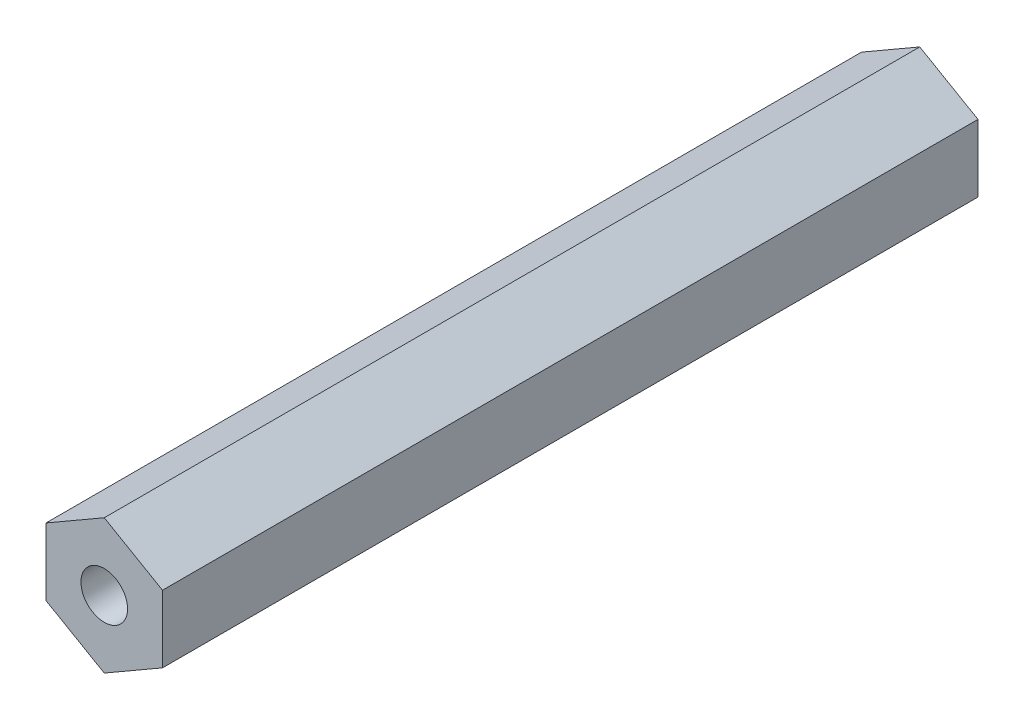
SolidWorks part; units mm, degrees
ref_plane "Front Plane" through (0, 0, 0) normal (0, 0, 1) x (1, 0, 0)
ref_plane "Top Plane" through (0, 0, 0) normal (0, 1, 0) x (1, 0, 0)
ref_plane "Right Plane" through (0, 0, 0) normal (1, 0, 0) x (0, 0, -1)
sketch "Sketch1" plane through (0, 0, 0) normal (0, 0, 1) x (1, 0, 0)
  line L1 (0, 2.8868) -> (-2.5, 1.4434)
  line L2 (-2.5, 1.4434) -> (-2.5, -1.4434)
  line L3 (-2.5, -1.4434) -> (0, -2.8868)
  line L4 (0, -2.8868) -> (2.5, -1.4434)
  line L5 (2.5, -1.4434) -> (2.5, 1.4434)
  line L6 (2.5, 1.4434) -> (0, 2.8868)
  circle A0 centre (0, 0) radius 2.5 construction
  circle A1 centre (0, 0) radius 1
  dimension "D1" = 5
  dimension "D2" = 2
extrude "Boss-Extrude1" add sketch "Sketch1" along normal blind 35
